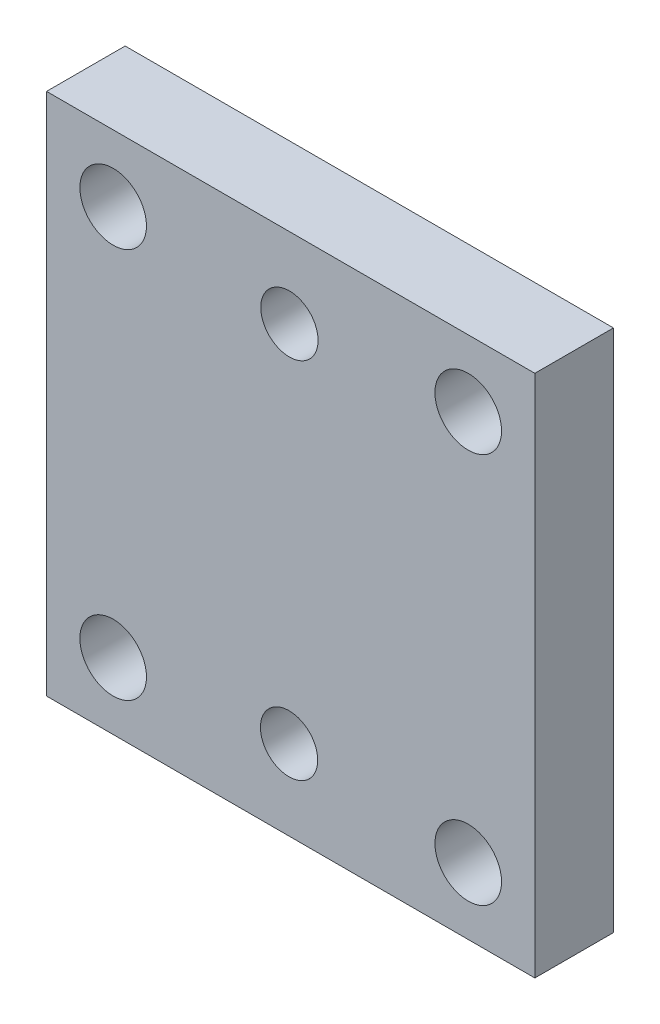
SolidWorks part; units mm, degrees
material "Custom Plastic"
ref_plane "Front Plane" through (0, 0, 0) normal (0, 0, 1) x (1, 0, 0)
ref_plane "Top Plane" through (0, 0, 0) normal (0, 1, 0) x (1, 0, 0)
ref_plane "Right Plane" through (0, 0, 0) normal (1, 0, 0) x (0, 0, -1)
sketch "Sketch1" plane through (0, 0, 0) normal (0, 0, 1) x (1, 0, 0)
  line L1 (-18.7132, 19.6563) -> (17.9418, 19.6563)
  line L2 (-18.7132, 19.6563) -> (-18.7132, -19.6563)
  line L3 (-18.7132, -19.6563) -> (17.9418, -19.6563)
  line L4 (17.9418, 19.6563) -> (17.9418, -19.6563)
  line L5 (-16.7132, -10.1219) -> (-16.7132, 10.0965) construction
  line L9 (17.9418, 3.1678) -> (17.9418, -3.2722) construction
  arc A0 (4.5212, 13.6525) -> (-5.4864, 13.6525) centre (-0.4826, 13.6525) ccw construction
  arc A1 (-5.5118, -13.6525) -> (4.4958, -13.6525) centre (-0.508, -13.6525) ccw construction
  circle A2 centre (-0.4826, 13.6525) radius 2.15
  circle A3 centre (-0.508, -13.6525) radius 2.15
  point P7 (-0.4826, 18.6563)
  point P11 (-0.508, -18.6563)
  point P25 (-0.508, 13.6525)
  dimension "D4" = 4.3
  dimension "D5" = 4.3
  dimension "D1" = 1
  dimension "D2" = 1
  dimension "D3" = 2
extrude "Boss-Extrude1" add sketch "Sketch1" along normal blind 4
sketch "Sketch2" plane through (0, 0, 0) normal (0, 0, -1) x (-1, 0, 0)
  line L0 (-17.1132, 10.4965) -> (-6.4649, 10.4965)
  line L1 (-6.4649, 10.4965) -> (-4.9212, 12.0402)
  line L2 (-4.9212, 13.6525) -> (-4.9212, 12.0402)
  line L3 (-6.2992, 10.0965) -> (-16.7132, 10.0965) construction
  line L4 (-6.2992, 10.0965) -> (-4.5212, 11.8745) construction
  line L5 (-4.5212, 13.6525) -> (-4.5212, 11.8745) construction
  line L6 (-6.2992, 10.0965) -> (-16.7132, 10.0965) construction
  line L7 (-6.2992, 10.0965) -> (-4.5212, 11.8745) construction
  line L8 (-4.5212, 13.6525) -> (-4.5212, 11.8745) construction
  line L9 (5.9372, 13.6525) -> (5.9372, 12.0402)
  line L10 (5.9372, 12.0402) -> (7.4809, 10.4965)
  line L11 (7.4809, 10.4965) -> (17.1132, 10.4965)
  line L12 (17.1132, 10.4965) -> (17.1132, -0.0127)
  line L15 (7.3152, 10.0965) -> (5.4864, 11.9253) construction
  line L16 (16.7132, 10.0965) -> (7.3152, 10.0965) construction
  line L17 (16.7132, -10.1219) -> (16.7132, 10.0965) construction
  line L18 (16.7132, -10.1219) -> (16.7132, 10.0965) construction
  line L19 (17.1132, -0.0127) -> (-17.9418, 0) construction
  line L20 (-17.9418, -19.6563) -> (-17.9418, 19.6563) construction
  line L21 (-17.1132, 10.4965) -> (-17.1132, -0.0003)
  line L22 (-16.7132, 10.0965) -> (-16.7132, -10.1219) construction
  line L23 (-17.1208, -10.4971) -> (-17.1132, -0.0003)
  line L24 (17.1056, -10.5219) -> (17.1132, -0.0127)
  line L25 (7.4733, -10.5149) -> (17.1056, -10.5219)
  line L26 (5.9285, -12.0575) -> (7.4733, -10.5149)
  line L27 (5.9273, -13.6698) -> (5.9285, -12.0575)
  line L28 (-4.9311, -13.6619) -> (-4.9299, -12.0496)
  line L29 (-6.4725, -10.5048) -> (-4.9299, -12.0496)
  line L30 (-17.1208, -10.4971) -> (-6.4725, -10.5048)
  line L32 (-17.9418, 19.6563) -> (18.7132, 19.6563)
  line L33 (-17.9418, 19.6563) -> (-17.9418, -19.6563)
  line L34 (-17.9418, -19.6563) -> (18.7132, -19.6563)
  line L35 (18.7132, 19.6563) -> (18.7132, -19.6563)
  arc A0 (-4.9212, 13.6525) -> (5.9372, 13.6525) centre (0.508, 13.6525) cw
  arc A1 (-4.9311, -13.6619) -> (5.9273, -13.6698) centre (0.4981, -13.6659) ccw
  point P33 (16.7132, -0.0127)
  point P55 (0, 0)
  point P58 (0.508, 13.6525)
  dimension "D1" = 0.4
  dimension "D2" = 0.4
  dimension "D3" = 0.4
  dimension "D4" = 0.4
  dimension "D5" = 0.4
  dimension "D6" = 0.4
  dimension "D7" = 0.4
extrude "Boss-Extrude2" add sketch "Sketch2" along normal offset from surface (1.9 mm away) 0.7
sketch "Sketch3" plane through (0, 0, -1.9) normal (0, 0, -1) x (-1, 0, 0)
  line L0 (18.7132, 19.6563) -> (-17.9418, 19.6563) construction
  line L1 (-17.9418, 19.6563) -> (-17.9418, -19.6563) construction
  line L2 (0.3857, 19.6563) -> (0.3857, -19.6563) construction
  line L3 (-17.9418, -19.6563) -> (18.7132, -19.6563) construction
  line L4 (18.7132, 0) -> (-17.9418, 0) construction
  line L5 (18.7132, -19.6563) -> (18.7132, 19.6563) construction
  circle A0 centre (-12.9418, 14.6563) radius 2.5
  circle A1 centre (13.7132, 14.6563) radius 2.5
  circle A2 centre (13.7132, -14.6563) radius 2.5
  circle A3 centre (-12.9418, -14.6563) radius 2.5
  dimension "D3" = 5
  dimension "D1" = 5
  dimension "D2" = 5
extrude "Cut-Extrude1" cut sketch "Sketch3" against normal up to surface (5.9 mm away) up to face at (1.6674, 13.6525, 4)
sketch "Sketch4" plane through (0, 0, 0) normal (0, 0, -1) x (-1, 0, 0)
  line L0 (16.8922, -5.8375) -> (7.822, -5.8375) construction
  line L1 (7.822, 5.265) -> (16.7132, 5.265)
  line L2 (7.822, 5.265) -> (7.822, -5.8375)
  line L3 (7.822, -5.8375) -> (16.7132, -5.8375)
  line L4 (16.7132, 5.265) -> (16.7132, -5.8375)
  line L5 (16.7132, -10.1219) -> (16.7132, 10.0965) construction
extrude "Cut-Extrude2" cut sketch "Sketch4" against normal blind 3
